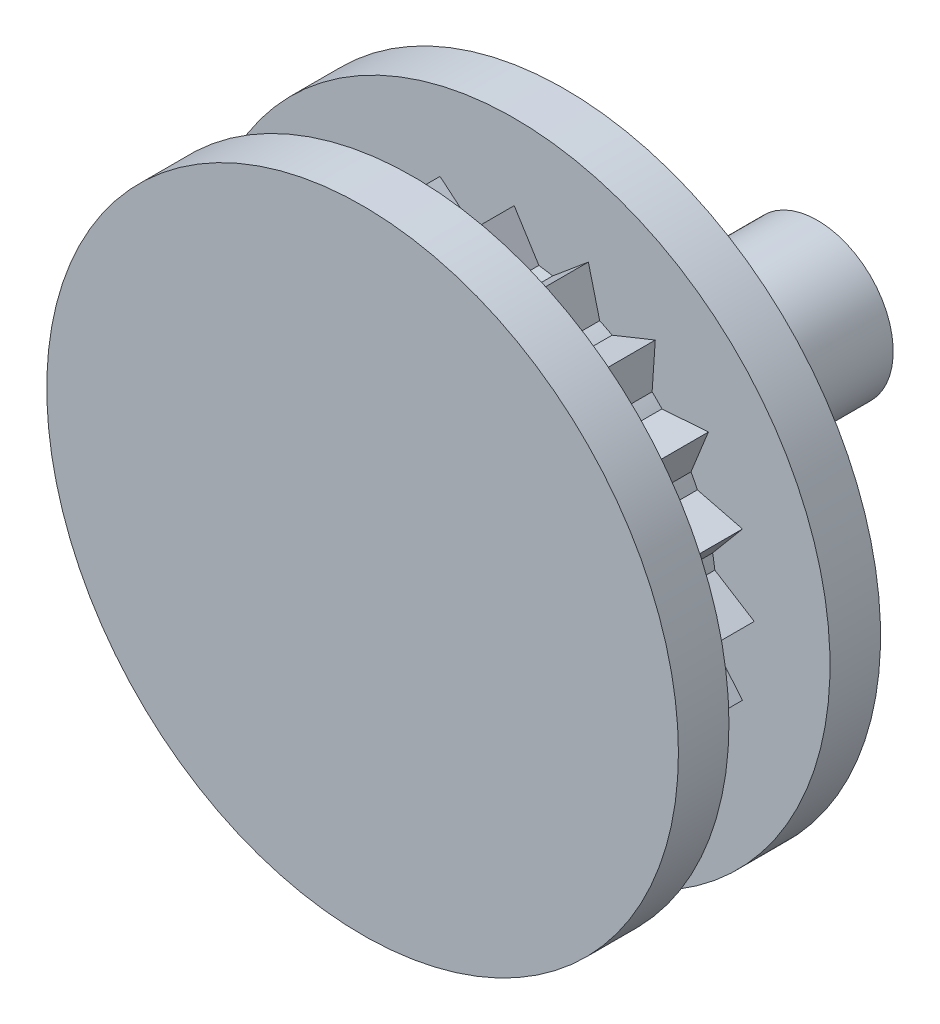
SolidWorks part; units mm, degrees
ref_plane "Front Plane" through (0, 0, 0) normal (0, 0, 1) x (1, 0, 0)
ref_plane "Top Plane" through (0, 0, 0) normal (0, 1, 0) x (1, 0, 0)
ref_plane "Right Plane" through (0, 0, 0) normal (1, 0, 0) x (0, 0, -1)
sketch "Sketch2" plane through (0, 0, 0) normal (0, 0, 1) x (1, 0, 0)
  line L0 (0, 9.5) -> (-0.9778, 7.94)
  line L1 (0, 18.5609) -> (0, 8) construction
  line L2 (0, 9.5) -> (0.9778, 7.94)
  line L3 (2.9357, 9.035) -> (1.5236, 7.8536)
  line L4 (2.9357, 9.035) -> (3.3836, 7.2492)
  line L5 (5.584, 7.6857) -> (3.8759, 6.9984)
  line L6 (5.584, 7.6857) -> (5.4581, 5.8489)
  line L7 (7.6857, 5.584) -> (5.8489, 5.4581)
  line L8 (7.6857, 5.584) -> (6.9984, 3.8759)
  line L9 (9.035, 2.9357) -> (7.2492, 3.3836)
  line L10 (9.035, 2.9357) -> (7.8536, 1.5236)
  line L11 (9.5, 0) -> (7.94, 0.9778)
  line L12 (9.5, 0) -> (7.94, -0.9778)
  line L13 (9.035, -2.9357) -> (7.8536, -1.5236)
  line L14 (9.035, -2.9357) -> (7.2492, -3.3836)
  line L15 (7.6857, -5.584) -> (6.9984, -3.8759)
  line L16 (7.6857, -5.584) -> (5.8489, -5.4581)
  line L17 (5.584, -7.6857) -> (5.4581, -5.8489)
  line L18 (5.584, -7.6857) -> (3.8759, -6.9984)
  line L19 (2.9357, -9.035) -> (3.3836, -7.2492)
  line L20 (2.9357, -9.035) -> (1.5236, -7.8536)
  line L21 (0, -9.5) -> (0.9778, -7.94)
  line L22 (0, -9.5) -> (-0.9778, -7.94)
  line L23 (-2.9357, -9.035) -> (-1.5236, -7.8536)
  line L24 (-2.9357, -9.035) -> (-3.3836, -7.2492)
  line L25 (-5.584, -7.6857) -> (-3.8759, -6.9984)
  line L26 (-5.584, -7.6857) -> (-5.4581, -5.8489)
  line L27 (-7.6857, -5.584) -> (-5.8489, -5.4581)
  line L28 (-7.6857, -5.584) -> (-6.9984, -3.8759)
  line L29 (-9.035, -2.9357) -> (-7.2492, -3.3836)
  line L30 (-9.035, -2.9357) -> (-7.8536, -1.5236)
  line L31 (-9.5, 0) -> (-7.94, -0.9778)
  line L32 (-9.5, 0) -> (-7.94, 0.9778)
  line L33 (-9.035, 2.9357) -> (-7.8536, 1.5236)
  line L34 (-9.035, 2.9357) -> (-7.2492, 3.3836)
  line L35 (-7.6857, 5.584) -> (-6.9984, 3.8759)
  line L36 (-7.6857, 5.584) -> (-5.8489, 5.4581)
  line L37 (-5.584, 7.6857) -> (-5.4581, 5.8489)
  line L38 (-5.584, 7.6857) -> (-3.8759, 6.9984)
  line L39 (-2.9357, 9.035) -> (-3.3836, 7.2492)
  line L40 (-2.9357, 9.035) -> (-1.5236, 7.8536)
  line L41 (0, -8) -> (0, -26.6445) construction
  circle A0 centre (0, 0) radius 9.5
  arc A1 (-3.8759, -6.9984) -> (-3.3836, -7.2492) centre (0, 0) ccw
  arc A2 (-5.8489, -5.4581) -> (-5.4581, -5.8489) centre (0, 0) ccw
  arc A3 (-7.2492, -3.3836) -> (-6.9984, -3.8759) centre (0, 0) ccw
  arc A4 (-7.8536, 1.5236) -> (-7.94, 0.9778) centre (0, 0) ccw
  arc A5 (-7.94, -0.9778) -> (-7.8536, -1.5236) centre (0, 0) ccw
  arc A6 (-6.9984, 3.8759) -> (-7.2492, 3.3836) centre (0, 0) ccw
  arc A7 (-5.4581, 5.8489) -> (-5.8489, 5.4581) centre (0, 0) ccw
  arc A8 (0.9778, -7.94) -> (1.5236, -7.8536) centre (0, 0) ccw
  arc A9 (-1.5236, -7.8536) -> (-0.9778, -7.94) centre (0, 0) ccw
  arc A10 (3.3836, -7.2492) -> (3.8759, -6.9984) centre (0, 0) ccw
  arc A11 (5.4581, -5.8489) -> (5.8489, -5.4581) centre (0, 0) ccw
  arc A12 (6.9984, -3.8759) -> (7.2492, -3.3836) centre (0, 0) ccw
  arc A13 (7.8536, -1.5236) -> (7.94, -0.9778) centre (0, 0) ccw
  arc A14 (7.94, 0.9778) -> (7.8536, 1.5236) centre (0, 0) ccw
  arc A15 (7.2492, 3.3836) -> (6.9984, 3.8759) centre (0, 0) ccw
  arc A16 (5.8489, 5.4581) -> (5.4581, 5.8489) centre (0, 0) ccw
  arc A17 (3.8759, 6.9984) -> (3.3836, 7.2492) centre (0, 0) ccw
  arc A18 (-0.9778, 7.94) -> (-1.5236, 7.8536) centre (0, 0) ccw
  arc A19 (-3.3836, 7.2492) -> (-3.8759, 6.9984) centre (0, 0) ccw
  arc A20 (1.5236, 7.8536) -> (0.9778, 7.94) centre (0, 0) ccw
  point P68 (0, 0)
  dimension "D1" = 19
  dimension "D2" = 16
  dimension "D3" = 20
extrude "Boss-Extrude1" add sketch "Sketch2" along normal blind 4 contours L3 A20 L2 L0 A18 L40 L39 A19 L38 L37 A7 L36 L35 A6 L34 L33 A4 L32 L31 A5 L30 L29 A3 L28 L27 A2 L26 L25 A1 L24 L23 A9 L22 L21 A8 L20 L19 A10 L18 L17 A11 L16 L15 A12 L14 L13 A13 L12 L11 A14 L10
sketch "Sketch3" plane through (0, 0, 4) normal (0, 0, 1) x (1, 0, 0)
  circle A0 centre (0, 0) radius 12.5
  dimension "D1" = 25
extrude "Boss-Extrude2" add sketch "Sketch3" along normal blind 2
sketch "Sketch4" plane through (0, 0, 0) normal (0, 0, -1) x (-1, 0, 0)
  circle A0 centre (0, 0) radius 12.5
extrude "Boss-Extrude3" add sketch "Sketch4" along normal blind 2
sketch "Sketch5" plane through (0, 0, -2) normal (0, 0, -1) x (-1, 0, 0)
  circle A0 centre (0, 0) radius 3
  dimension "D1" = 6
extrude "Boss-Extrude4" add sketch "Sketch5" along normal blind 10
sketch "Sketch6" plane through (0, 0, -2) normal (0, 0, -1) x (-1, 0, 0)
  circle A0 centre (0, 0) radius 5
  circle A1 centre (0, 0) radius 3
  dimension "D1" = 10
extrude "Boss-Extrude5" add sketch "Sketch6" along normal blind 2
